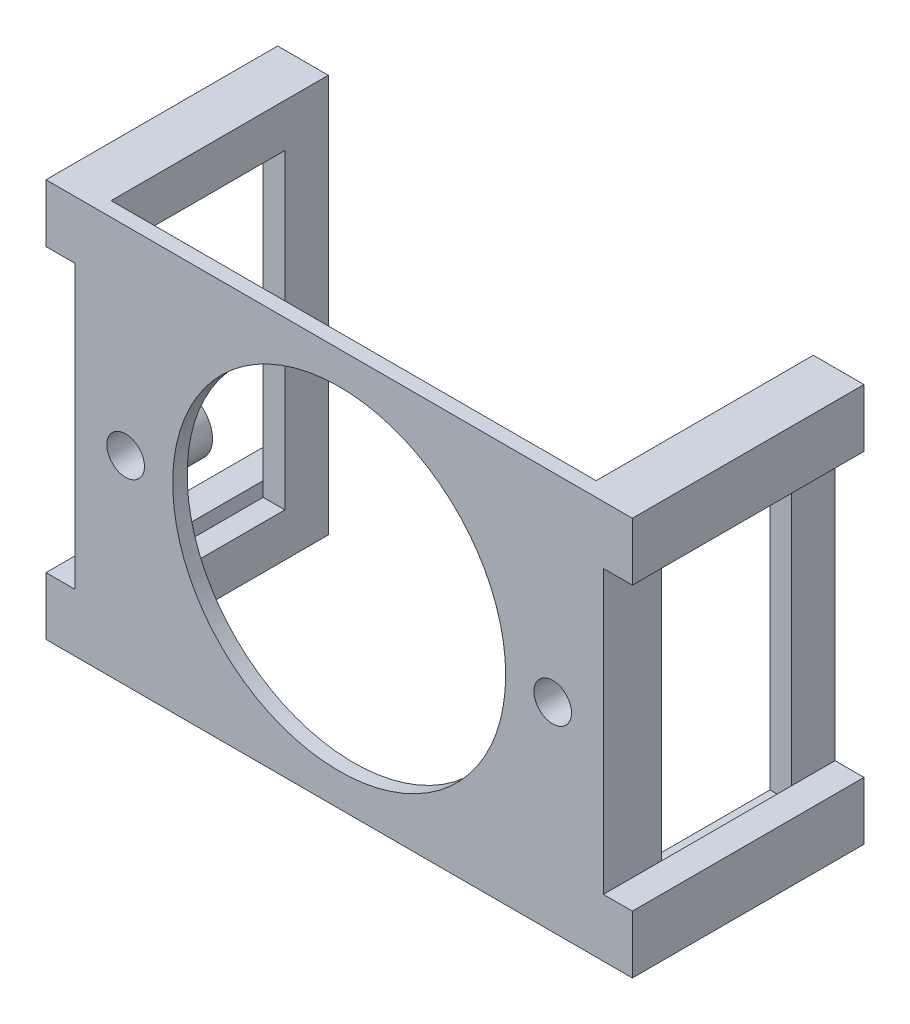
SolidWorks part; units mm, degrees
ref_plane "Front Plane" through (0, 0, 0) normal (0, 0, 1) x (1, 0, 0)
ref_plane "Top Plane" through (0, 0, 0) normal (0, 1, 0) x (1, 0, 0)
ref_plane "Right Plane" through (0, 0, 0) normal (1, 0, 0) x (0, 0, -1)
sketch "Sketch2" plane through (0, 0, 0) normal (0, 0, 1) x (1, 0, 0)
  line L0 (-18.25, 13.75) -> (-18.25, -13.75)
  line L1 (-16.25, 11.75) -> (16.25, 11.75) construction
  line L2 (-16.25, 11.75) -> (-16.25, -11.75) construction
  line L3 (-16.25, -11.75) -> (16.25, -11.75) construction
  line L4 (16.25, 11.75) -> (16.25, -11.75) construction
  line L5 (-16.25, 11.75) -> (16.25, -11.75) construction
  line L6 (-16.25, -11.75) -> (16.25, 11.75) construction
  line L7 (-18.25, -13.75) -> (18.25, -13.75)
  line L8 (18.25, 13.75) -> (18.25, -13.75)
  line L9 (-18.25, 13.75) -> (18.25, 13.75)
  line L10 (-18.25, 0) -> (18.25, 0) construction
  circle A0 centre (0, 0) radius 11.5
  circle A1 centre (-14.75, 0) radius 1.3
  circle A3 centre (14.75, 0) radius 1.3
  point P0 (0, 0)
  dimension "D1" = 23
  dimension "D5" = 2.6
  dimension "D6" = 1.5
  dimension "D2" = 32.5
  dimension "D3" = 23.5
  dimension "D7" = 1.5
  dimension "D4" = 2
extrude "Boss-Extrude1" add sketch "Sketch2" against normal blind 1
sketch "Sketch4" plane through (0, 0, -1) normal (0, 0, -1) x (-1, 0, 0)
  line L0 (-16.75, 13.75) -> (-16.75, 4)
  line L1 (-18.25, 13.75) -> (18.25, 13.75) construction
  line L2 (18.25, -13.75) -> (-18.25, -13.75) construction
  line L3 (-18.25, -13.75) -> (-18.25, 13.75) construction
  line L4 (-16.75, 13.75) -> (-18.25, 13.75)
  line L5 (-18.25, 13.75) -> (-18.25, -13.75)
  line L6 (-18.25, -13.75) -> (-16.75, -13.75)
  line L7 (-16.75, -4) -> (-16.75, -13.75)
  arc A0 (-14.75, -2) -> (-14.75, 2) centre (-14.75, 0) ccw
  arc A1 (-14.75, -2) -> (-16.75, -4) centre (-14.75, -4) ccw
  arc A2 (-16.75, 4) -> (-14.75, 2) centre (-14.75, 4) ccw
  circle A4 centre (-14.75, 0) radius 1.3 construction
  circle A5 centre (-14.75, 0) radius 1.3
  dimension "D1" = 1.5
extrude "Boss-Extrude2" add sketch "Sketch4" along normal blind 3 contours A2 A0 A1 L7 L6 L5 L4 L0
sketch "Sketch5" plane through (0, 0, -4) normal (0, 0, -1) x (-1, 0, 0)
  line L1 (-18.25, 13.75) -> (-16.75, 13.75)
  line L2 (-18.25, 13.75) -> (-18.25, -13.75)
  line L3 (-18.25, -13.75) -> (-16.75, -13.75)
  line L4 (-16.75, 13.75) -> (-16.75, -13.75)
extrude "Boss-Extrude3" add sketch "Sketch5" along normal blind 12
sketch "Sketch6" plane through (18.25, 0, 0) normal (1, 0, 0) x (0, 0, -1)
  line L4 (16, -13.75) -> (0, -13.75) construction
  line L5 (16, 13.75) -> (1, 13.75)
  line L6 (16, 13.75) -> (16, -13.75)
  line L7 (16, -13.75) -> (1, -13.75)
  line L8 (1, 13.75) -> (1, -13.75)
  line L10 (4, -4) -> (4, 4) construction
  line L11 (13, 10.75) -> (13, -10.75)
  line L12 (13, -10.75) -> (4, -10.75)
  line L13 (4, 10.75) -> (4, -10.75)
  line L14 (13, 10.75) -> (4, 10.75)
  dimension "D1" = 3
  dimension "D2" = 3
extrude "Cut-Extrude1" cut sketch "Sketch6" against normal up to surface (1.5 mm away) contours L11 L12 L13 L14 up to face at (16.75, 0, -5.5)
sketch "Sketch7" plane through (0, 0, -16) normal (0, 0, -1) x (-1, 0, 0)
  line L0 (-18.25, 13.75) -> (-20.25, 13.75)
  line L1 (-18.25, 13.75) -> (-18.25, -13.75) construction
  line L2 (-20.25, 13.75) -> (-20.25, 9.75)
  line L3 (-20.25, 9.75) -> (-18.25, 9.75)
  line L4 (-18.25, 9.75) -> (-18.25, 13.75)
  line L5 (-16.75, 13.75) -> (-18.25, 13.75) construction
  line L6 (55, 0) -> (-55, 0) construction
  line L7 (-20.25, -9.75) -> (-18.25, -9.75)
  line L8 (-20.25, -13.75) -> (-20.25, -9.75)
  line L9 (-18.25, -13.75) -> (-20.25, -13.75)
  line L10 (-18.25, -9.75) -> (-18.25, -13.75)
  point P4 (-18.25, 13.75)
  point P7 (-18.25, 13.75)
  point P9 (-18.25, 10.7334)
  point P16 (-18.25, 13.75)
  point P17 (-18.25, 13.75)
  dimension "D1" = 4
  dimension "D2" = 2
extrude "Boss-Extrude4" add sketch "Sketch7" against normal up to surface (16 mm away) up to face at (16.05, 0, 0)
mirror "Mirror1" about plane through (0, 0, 0) normal (1, 0, 0) of "Boss-Extrude2", "Boss-Extrude4", "Cut-Extrude1", "Boss-Extrude3"
